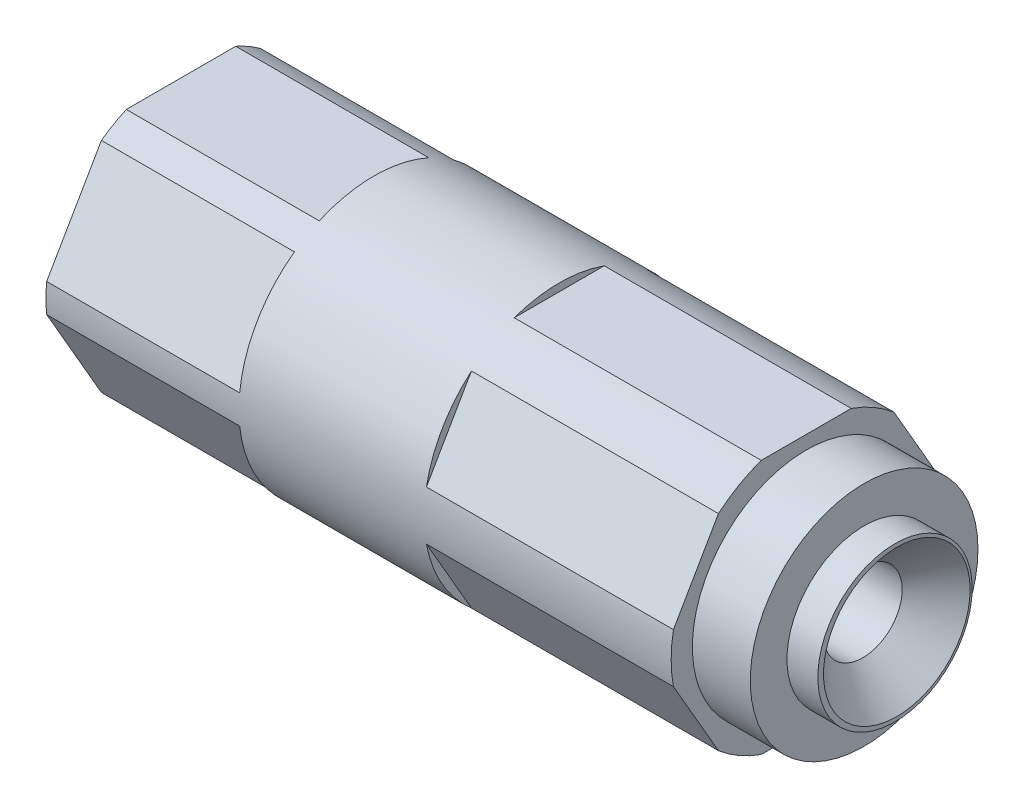
SolidWorks part; units mm, degrees
material "Plain Carbon Steel"
ref_plane "Front Plane" through (0, 0, 0) normal (0, 0, 1) x (1, 0, 0)
ref_plane "Top Plane" through (0, 0, 0) normal (0, 1, 0) x (1, 0, 0)
ref_plane "Right Plane" through (0, 0, 0) normal (1, 0, 0) x (0, 0, -1)
sketch "Sketch1" plane through (0, 0, 0) normal (0, 0, 1) x (1, 0, 0)
  line L0 (0, 0) -> (0, 17.5)
  line L1 (0, 17.5) -> (81, 17.5)
  line L2 (81, 17.5) -> (81, 14.75)
  line L3 (81, 0) -> (0, 0)
  line L4 (0, 0) -> (-29.537, 0) construction
  line L5 (81, 14.75) -> (88.5, 14.75)
  line L6 (88.5, 14.75) -> (88.5, 10)
  line L7 (88.5, 10) -> (92.5, 10)
  line L8 (92.5, 10) -> (92.5, 0)
  line L9 (92.5, 0) -> (81, 0)
  dimension "D1" = 35
  dimension "D2" = 81
  dimension "D3" = 29.5
  dimension "D4" = 20
  dimension "D5" = 7.5
  dimension "D6" = 4
revolve "Revolve1" add sketch "Sketch1" angle 360 about L4
sketch "Sketch5" plane through (0, 0, 0) normal (-1, 0, 0) x (0, 0, 1)
  line L1 (9.2376, 16) -> (-9.2376, 16)
  line L2 (-9.2376, 16) -> (-18.4752, 0)
  line L3 (-18.4752, 0) -> (-9.2376, -16)
  line L4 (-9.2376, -16) -> (9.2376, -16)
  line L5 (9.2376, -16) -> (18.4752, 0)
  line L6 (18.4752, 0) -> (9.2376, 16)
  circle A0 centre (0, 0) radius 16 construction
  dimension "D1" = 32
extrude "Cut-Extrude3" cut sketch "Sketch5" against normal blind 25 flip side to cut
hole_wizard "M10x1.5 Tapped Hole1" positions "Sketch8" profile "Sketch7" tap size "M10x1.5" standard "BSI"
sketch "Sketch8" plane through (0, 0, 0) normal (-1, 0, 0) x (0, 0, 1)
  point P0 (0, 0)
sketch "Sketch7" plane through (0, 0, 0) normal (0, 1, 0) x (0, 0, 1)
  line L0 (0, 0) -> (0, 27.0537)
  line L1 (0, 27.0537) -> (4.25, 24.5)
  line L2 (4.25, 24.5) -> (4.25, 0)
  line L5 (4.25, 0) -> (0, 0)
  line L10 (0, 27.0537) -> (-4.25, 24.5) construction
  line L11 (0, -6.35) -> (0, 107.95) construction
  dimension "Tap Drill Dia." = 8.5
  dimension "Tap Drill Depth" = 24.5
  dimension "Drill Angle" = 118
cosmetic thread "Hole Thread1" parameters "D1"=20, "D2"=10
sketch "Sketch9" plane through (81, 0, 0) normal (1, 0, 0) x (0, 0, -1)
  line L1 (-9.5263, -16.5) -> (9.5263, -16.5)
  line L2 (9.5263, -16.5) -> (19.0526, 0)
  line L3 (19.0526, 0) -> (9.5263, 16.5)
  line L4 (9.5263, 16.5) -> (-9.5263, 16.5)
  line L5 (-9.5263, 16.5) -> (-19.0526, 0)
  line L6 (-19.0526, 0) -> (-9.5263, -16.5)
  circle A0 centre (0, 0) radius 16.5 construction
  dimension "D1" = 33
extrude "Cut-Extrude5" cut sketch "Sketch9" against normal blind 32 flip side to cut
hole_wizard "M12x1.75 Tapped Hole1" positions "Sketch11" profile "Sketch10" tap size "M12x1.75" standard "BSI"
sketch "Sketch11" plane through (92.5, 0, 0) normal (1, 0, 0) x (0, 0, -1)
  point P0 (0.2318, -0.025)
sketch "Sketch10" plane through (92.5, -0.025, -0.2318) normal (0, 1, 0) x (0, 0, -1)
  line L0 (0, 0) -> (0, 32.3144)
  line L1 (0, 32.3144) -> (5.1, 29.25)
  line L2 (5.1, 29.25) -> (5.1, 4.4)
  line L3 (5.1, 4.4) -> (9.5, 0)
  line L5 (9.5, 0) -> (0, 0)
  line L6 (-5.1, 4.4) -> (-9.5, 0) construction
  line L10 (0, 32.3144) -> (-5.1, 29.25) construction
  line L11 (0, -6.35) -> (0, 107.95) construction
  dimension "Tap Drill Dia." = 10.2
  dimension "Tap Drill Depth" = 29.25
  dimension "Near C'Sink Dia." = 19
  dimension "Near C'Sink Angle" = 90
  dimension "Drill Angle" = 118
cosmetic thread "Hole Thread2" parameters "D1"=24, "D2"=12
